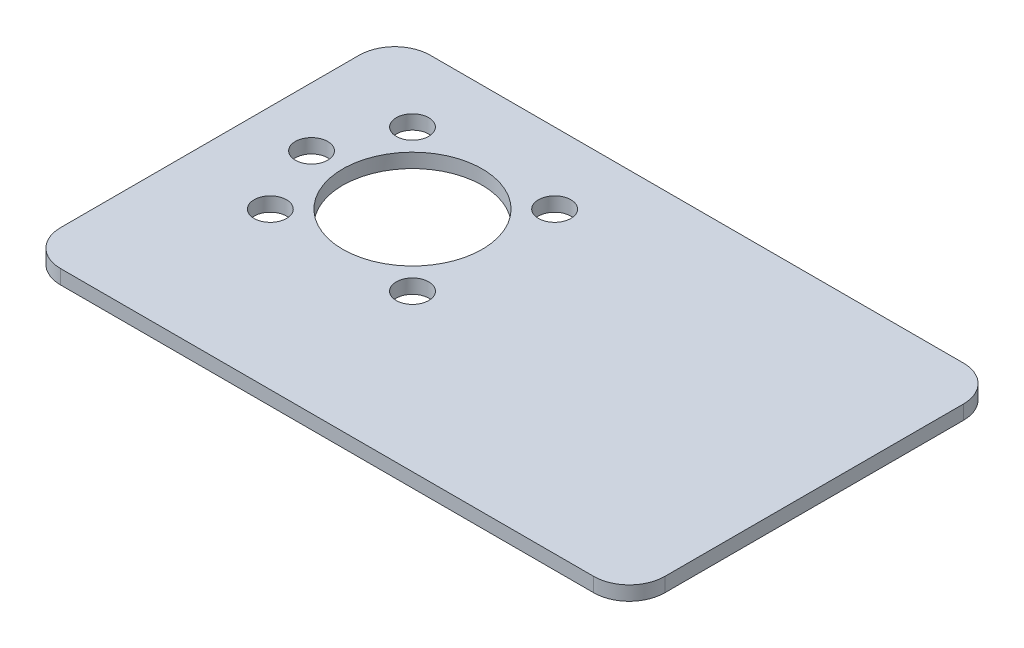
SolidWorks part; units mm, degrees
material "6061 Alloy"
ref_plane "Front Plane" through (0, 0, 0) normal (0, 0, 1) x (1, 0, 0)
ref_plane "Top Plane" through (0, 0, 0) normal (0, 1, 0) x (1, 0, 0)
ref_plane "Right Plane" through (0, 0, 0) normal (1, 0, 0) x (0, 0, -1)
sketch "Sketch1" plane through (0, 0, 0) normal (0, 1, 0) x (1, 0, 0)
  line L0 (0, 40.64) -> (107.95, 40.64) construction
  line L5 (0, 0) -> (107.95, 0)
  line L6 (0, 0) -> (0, 66.04)
  line L7 (0, 66.04) -> (107.95, 66.04)
  line L8 (107.95, 0) -> (107.95, 66.04)
  line L9 (15.875, 53.34) -> (41.275, 53.34) construction
  line L10 (15.875, 53.34) -> (15.875, 27.94) construction
  line L11 (15.875, 27.94) -> (41.275, 27.94) construction
  line L12 (41.275, 53.34) -> (41.275, 27.94) construction
  line L13 (28.575, 53.34) -> (28.575, 27.94) construction
  point P10 (15.875, 40.64)
  point P12 (28.575, 40.64)
  point P15 (0, 0)
  point P16 (0, 0)
  dimension "D1" = 107.95
  dimension "D2" = 66.04
  dimension "D3" = 25.4
  dimension "D4" = 25.4
  dimension "D5" = 15.875
extrude "Boss-Extrude1" add sketch "Sketch1" along normal blind 2.54
sketch "Sketch4" plane through (0, 2.54, 0) normal (0, 1, 0) x (1, 0, 0)
  line L0 (0, 40.64) -> (107.95, 40.64) construction
  point P0 (15.875, 53.34)
  point P3 (41.275, 53.34)
  point P6 (41.275, 27.94)
  point P9 (15.875, 27.94)
  point P28 (10.541, 40.64)
  dimension "D1" = 18.034
hole_wizard "M5 Clearance Hole1" positions "Sketch4" profile "Sketch3" hole size "M5" standard "ANSI Metric" end condition up to next
sketch "Sketch3" plane through (15.875, 2.54, -53.34) normal (1, 0, 0) x (0, 0, 1)
  line L0 (0, 0) -> (0, 2.54)
  line L1 (0, 2.54) -> (2.9, 2.54)
  line L2 (2.9, 2.54) -> (2.9, 0)
  line L5 (2.9, 0) -> (0, 0)
  line L11 (0, -6.35) -> (0, 107.95) construction
  dimension "Thru Hole Dia." = 5.8
  dimension "Thru Hole Depth" = 2.54
sketch "Sketch9" plane through (0, 2.54, 0) normal (0, 1, 0) x (1, 0, 0)
  point P0 (28.575, 40.64)
  point P5 (0, 0)
  point P6 (0, 0)
  point P10 (0, 0)
hole_wizard "#97 (0.981) Diameter Hole1" positions "Sketch9" profile "Sketch8" hole size "#97" standard "ANSI Inch" end condition up to next
sketch "Sketch8" plane through (28.575, 2.54, -40.64) normal (1, 0, 0) x (0, 0, 1)
  line L0 (0, 0) -> (0, 2.54)
  line L1 (0, 2.54) -> (12.4587, 2.54)
  line L2 (12.4587, 2.54) -> (12.4587, 0)
  line L5 (12.4587, 0) -> (0, 0)
  line L11 (0, -6.35) -> (0, 107.95) construction
  dimension "Thru Hole Dia." = 24.9174
  dimension "Thru Hole Depth" = 2.54
fillet "Fillet1" radius 6.35 4 edges at (0, 1.27, -66.04) (0, 1.27, 0) (107.95, 1.27, 0) (107.95, 1.27, -66.04)
